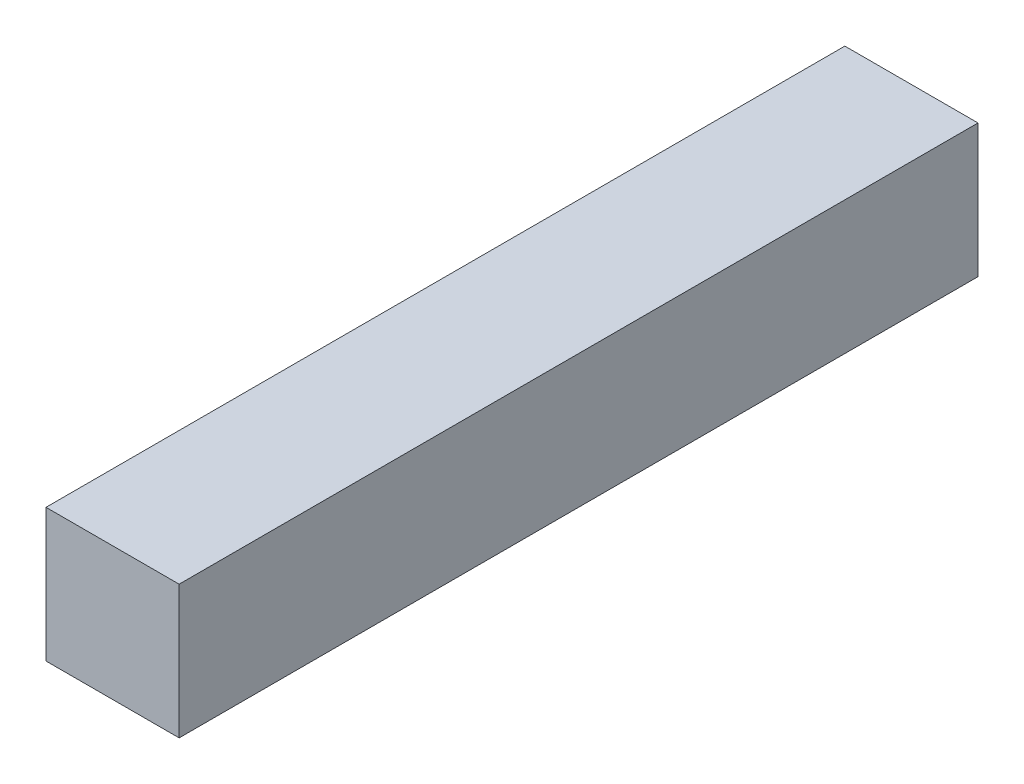
SolidWorks part; units mm, degrees
ref_plane "Front Plane" through (0, 0, 0) normal (0, 0, 1) x (1, 0, 0)
ref_plane "Top Plane" through (0, 0, 0) normal (0, 1, 0) x (1, 0, 0)
ref_plane "Right Plane" through (0, 0, 0) normal (1, 0, 0) x (0, 0, -1)
sketch "Sketch1" plane through (0, 0, 0) normal (0, 0, 1) x (1, 0, 0)
  line L1 (-1.5, -1.5) -> (1.5, -1.5)
  line L2 (-1.5, -1.5) -> (-1.5, 1.5)
  line L3 (-1.5, 1.5) -> (1.5, 1.5)
  line L4 (1.5, -1.5) -> (1.5, 1.5)
  line L5 (-1.5, -1.5) -> (1.5, 1.5) construction
  line L6 (-1.5, 1.5) -> (1.5, -1.5) construction
  point P0 (0, 0)
  dimension "D1" = 3
  dimension "D2" = 3
extrude "Boss-Extrude1" add sketch "Sketch1" along normal blind 18
